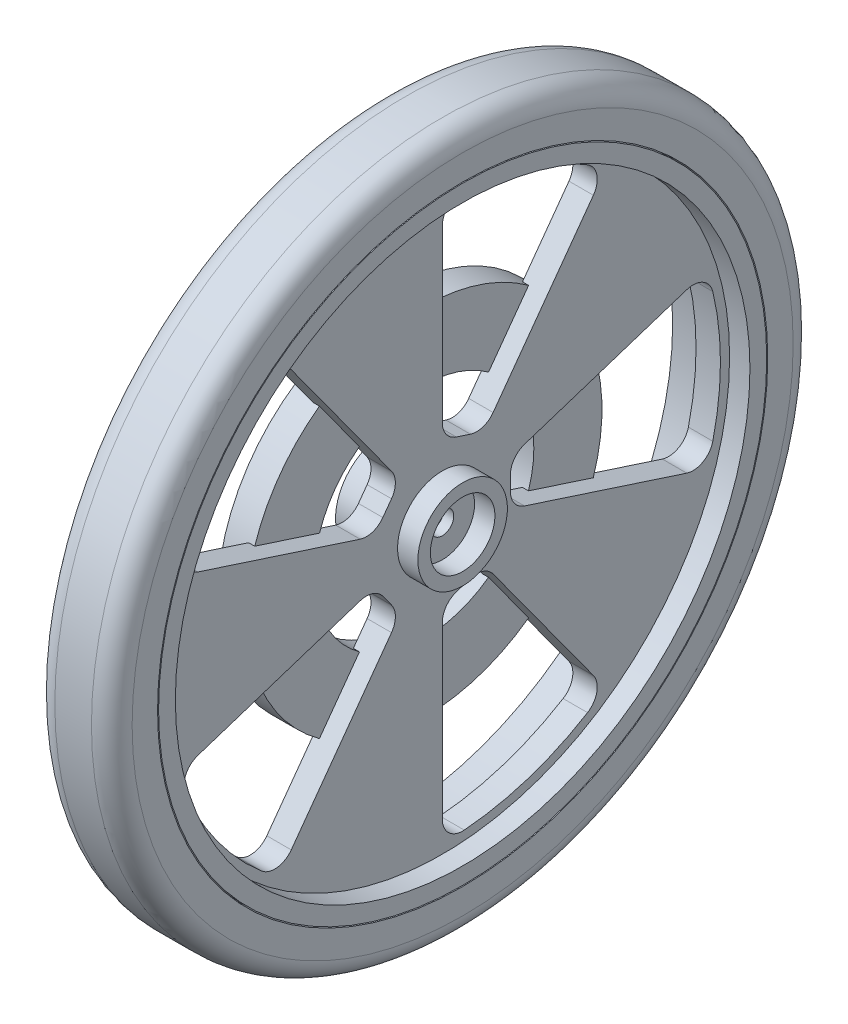
SolidWorks part; units mm, degrees
material "ABS PC"
ref_plane "Front Plane" through (0, 0, 0) normal (0, 0, 1) x (1, 0, 0)
ref_plane "Top Plane" through (0, 0, 0) normal (0, 1, 0) x (1, 0, 0)
ref_plane "Right Plane" through (0, 0, 0) normal (1, 0, 0) x (0, 0, -1)
sketch "Sketch1" plane through (0, 0, 0) normal (0, 0, 1) x (1, 0, 0)
  line L0 (0, 0) -> (0, 34.5) construction
  line L1 (-1.8, 34.5) -> (1.8, 34.5)
  line L2 (3.8, 32.5) -> (3.8, 30)
  line L3 (3.8, 30) -> (1.8, 30)
  line L4 (1.8, 30) -> (1.8, 29.9)
  line L5 (1.8, 29.9) -> (3.8, 29.9)
  line L6 (3.8, 29.9) -> (3.8, 28.25)
  line L7 (3.8, 28.25) -> (1.8, 28.25)
  line L8 (1.8, 28.25) -> (1.8, 3.5)
  line L9 (1.8, 3.5) -> (-1.8, 3.5)
  line L10 (-1.8, 28.25) -> (-1.8, 3.5)
  line L11 (-3.8, 28.25) -> (-1.8, 28.25)
  line L12 (-3.8, 29.9) -> (-3.8, 28.25)
  line L13 (-1.8, 29.9) -> (-3.8, 29.9)
  line L14 (-1.8, 30) -> (-1.8, 29.9)
  line L15 (-3.8, 30) -> (-1.8, 30)
  line L16 (-3.8, 32.5) -> (-3.8, 30)
  line L17 (0, 0) -> (12.5918, 0) construction
  arc A0 (3.8, 32.5) -> (1.8, 34.5) centre (1.8, 32.5) ccw
  arc A1 (-1.8, 34.5) -> (-3.8, 32.5) centre (-1.8, 32.5) ccw
  point P13 (0, 3.5)
  point P23 (3.8, 34.5)
  point P26 (-3.8, 34.5)
  dimension "D8" = 2
  dimension "D1" = 34.5
  dimension "D2" = 4.5
  dimension "D3" = 28.25
  dimension "D4" = 2
  dimension "D5" = 3.8
  dimension "D6" = 0.1
  dimension "D7" = 3.5
revolve "Revolve1" add sketch "Sketch1" angle 360 about L17
sketch "Sketch3" plane through (1.8, 0, 0) normal (1, 0, 0) x (0, 0, -1)
  line L0 (0, 7.0448) -> (0, 27.35)
  line L1 (4.1408, 5.6994) -> (16.0759, 22.1266)
  line L2 (0, 0) -> (19.8003, 0) construction
  line L3 (2.0704, 6.3721) -> (0, 0) construction
  line L4 (0, 7.0448) -> (4.1408, 5.6994)
  line L5 (4.1408, 5.6994) -> (0, 0) construction
  line L6 (0, 7.0448) -> (0, 0) construction
  arc A0 (0, 27.35) -> (16.0759, 22.1266) centre (0, 0) cw
  dimension "D2" = 27.35
  dimension "D1" = 36
  dimension "D3" = 6.7
extrude "Extrude1" cut sketch "Sketch3" against normal blind 20
fillet "Fillet1" radius 2 4 edges at (0, 22.1266, -16.0759) (0, 5.6994, -4.1408) (0, 7.0448, 0) (0, 27.35, 0)
pattern_circular "CirPattern1" count 5 over 360 about axis through (0, 0, 0) along (1, 0, 0) of "Fillet1", "Extrude1"
sketch "Sketch4" plane through (-1.8, 0, 0) normal (-1, 0, 0) x (0, 0, 1)
  circle A0 centre (0, 0) radius 28.25
extrude "Extrude2" cut sketch "Sketch4" against normal blind 1.2
sketch "Sketch5" plane through (0, 0, 0) normal (0, 0, 1) x (1, 0, 0)
  line L0 (-2.8, 17.5) -> (-2.8, 16.57)
  line L1 (-2.8, 16.57) -> (-0.6, 16.57)
  line L2 (-0.6, 16.57) -> (-0.6, 11.44)
  line L3 (-0.6, 11.44) -> (-2.3, 11.44)
  line L4 (-2.3, 11.44) -> (-2.3, 10.8)
  line L5 (-2.3, 10.8) -> (0, 10.8)
  line L6 (0, 10.8) -> (0, 17.5)
  line L7 (0, 17.5) -> (-2.8, 17.5)
  line L8 (-3.8, 32.5) -> (-3.8, -32.5) construction
  line L9 (0, 0) -> (7.8218, 0) construction
  dimension "D1" = 0.93
  dimension "D2" = 0.64
  dimension "D3" = 6.7
  dimension "D4" = 2.2
  dimension "D5" = 1.5
  dimension "D6" = 1
  dimension "D7" = 17.5
revolve "Revolve2" add sketch "Sketch5" angle 360 about L9
sketch "Sketch6" plane through (-0.6, 0, 0) normal (-1, 0, 0) x (0, 0, 1)
  line L0 (2.38, 2.5662) -> (2.38, -2.5662)
  line L2 (-2.38, 2.5662) -> (-2.38, -2.5662)
  circle A0 centre (0, 0) radius 4.9
  arc A1 (2.38, 2.5662) -> (-2.38, 2.5662) centre (0, 0) ccw
  arc A2 (-2.38, -2.5662) -> (2.38, -2.5662) centre (0, 0) ccw
  dimension "D1" = 9.8
  dimension "D3" = 3.5
  dimension "D2" = 4.76
extrude "Extrude3" add sketch "Sketch6" along normal up to surface and the other way up to surface
sketch "Sketch7" plane through (1.8, 0, 0) normal (1, 0, 0) x (0, 0, -1)
  circle A0 centre (0, 0) radius 1.125
  circle A1 centre (0, 0) radius 5.0234
  dimension "D1" = 2.25
extrude "Extrude4" add sketch "Sketch7" against normal blind 1
sketch "Sketch8" plane through (1.8, 0, 0) normal (1, 0, 0) x (0, 0, -1)
  circle A0 centre (0, 0) radius 3.175
  circle A1 centre (0, 0) radius 4.4
  dimension "D1" = 8.8
  dimension "D2" = 6.35
extrude "Extrude5" add sketch "Sketch8" along normal up to surface (2 mm away) up to face at (3.8, 0, 29.9)
sketch "Sketch9" plane through (-0.6, 0, 0) normal (-1, 0, 0) x (0, 0, 1)
  line L0 (-1.1446, 17.4625) -> (-0.7482, 11.4155)
  line L1 (-0.7482, 11.4155) -> (0.7482, 11.4155)
  line L2 (0.7482, 11.4155) -> (1.1446, 17.4625)
  line L3 (1.1446, 17.4625) -> (-1.1446, 17.4625)
  line L4 (0.7482, 11.4155) -> (0, 0) construction
  line L5 (0, 0) -> (-0.7482, 11.4155) construction
  circle A0 centre (0, 0) radius 17.5 construction
  circle A5 centre (0, 0) radius 11.44 construction
  circle A6 centre (0, 0) radius 11.44 construction
  dimension "D1" = 7.5
extrude "Extrude6" add sketch "Sketch9" along normal blind 0.2
pattern_circular "CirPattern2" count 24 over 360 about axis through (0, 0, 0) along (1, 0, 0) of "Extrude6"
